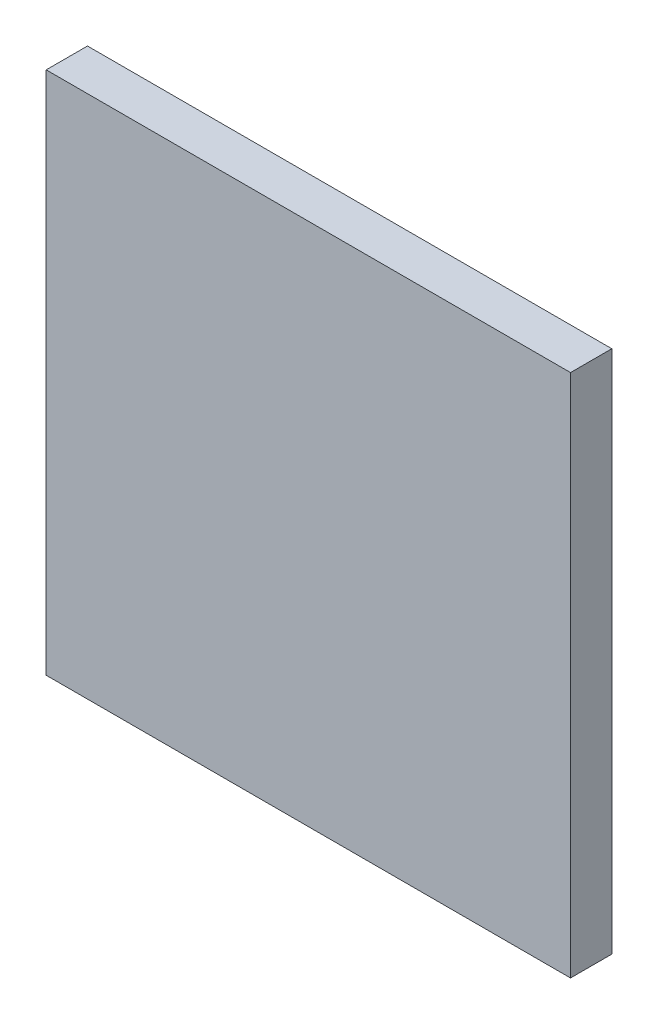
SolidWorks part; units mm, degrees
material "Maple"
ref_plane "Front Plane" through (0, 0, 0) normal (0, 0, 1) x (1, 0, 0)
ref_plane "Top Plane" through (0, 0, 0) normal (0, 1, 0) x (1, 0, 0)
ref_plane "Right Plane" through (0, 0, 0) normal (1, 0, 0) x (0, 0, -1)
sketch "Sketch1" plane through (0, 0, 0) normal (0, 0, 1) x (1, 0, 0)
  line L1 (0, 0) -> (-50.8, 0)
  line L2 (0, 0) -> (0, 50.8)
  line L3 (0, 50.8) -> (-50.8, 50.8)
  line L4 (-50.8, 0) -> (-50.8, 50.8)
  dimension "D1" = 50.8
  dimension "D2" = 50.8
extrude "Boss-Extrude1" add sketch "Sketch1" along normal blind 4 contours L3 L4 L1 L2
